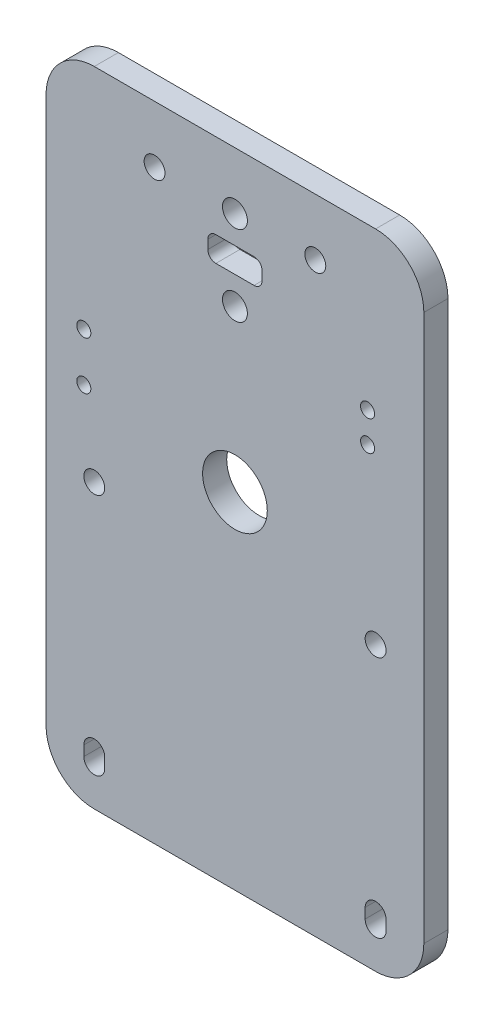
SolidWorks part; units mm, degrees
material "Polycarbonate (PC)"
ref_plane "Спереди" through (0, 0, 0) normal (0, 0, 1) x (1, 0, 0)
ref_plane "Сверху" through (0, 0, 0) normal (0, 1, 0) x (1, 0, 0)
ref_plane "Справа" through (0, 0, 0) normal (1, 0, 0) x (0, 0, -1)
sketch "Model" plane through (0, 0, 0) normal (0, 0, 1) x (1, 0, 0)
  line L5 (0, 170.1561) -> (0, 0) construction
  line L24 (-35, 37.2847) -> (-35, 78.8619) construction
  line L25 (-31.4983, 12.5) -> (-38.4, 12.5) construction
  line L26 (-31.4983, 10) -> (-38.4, 10) construction
  line L27 (-35, 12.5) -> (-35, 10) construction
  line L28 (-32.4, 12.5) -> (-32.4, 10)
  line L29 (-37.6, 12.5) -> (-37.6, 10)
  line L40 (31.4983, 10) -> (38.4, 10) construction
  line L41 (31.4983, 12.5) -> (38.4, 12.5) construction
  line L42 (35, 37.2847) -> (35, 78.8619) construction
  line L43 (35, 12.5) -> (35, 10) construction
  line L44 (32.4, 12.5) -> (32.4, 10)
  line L45 (37.6, 12.5) -> (37.6, 10)
  line L47 (-26.0102, 145.8) -> (26.0946, 145.8) construction
  line L50 (-20, 133.6948) -> (-20, 127.8457) construction
  line L51 (-38.85, 70.45) -> (-29.8907, 70.45) construction
  line L53 (-16.3166, 125.8) -> (17.7871, 125.8) construction
  line L58 (38.85, 70.45) -> (29.8907, 70.45) construction
  line L4875 (-35, 160) -> (35, 160)
  line L4882 (47, 148) -> (47, 12)
  line L4889 (35, 0) -> (-35, 0)
  line L4896 (-47, 12) -> (-47, 148)
  line L6648 (-6.75, 138.9) -> (6.75, 138.9)
  line L6649 (6.75, 138.9) -> (6.75, 132.7)
  line L6650 (6.75, 132.7) -> (-6.75, 132.7)
  line L6651 (-6.75, 132.7) -> (-6.75, 138.9)
  arc A0 (-47, 12) -> (-35, 0) centre (-35, 12) ccw
  arc A1 (35, 0) -> (47, 12) centre (35, 12) ccw
  arc A2 (47, 148) -> (35, 160) centre (35, 148) ccw
  arc A3 (-35, 160) -> (-47, 148) centre (-35, 148) ccw
  arc A13 (-32.4, 12.5) -> (-37.6, 12.5) centre (-35, 12.5) ccw
  arc A14 (-37.6, 10) -> (-32.4, 10) centre (-35, 10) ccw
  arc A19 (32.4, 12.5) -> (37.6, 12.5) centre (35, 12.5) cw
  arc A20 (37.6, 10) -> (32.4, 10) centre (35, 10) cw
  circle A29 centre (0, 145.8) radius 3.1
  circle A30 centre (-20, 145.8) radius 2.6
  circle A31 centre (20, 145.8) radius 2.6
  circle A32 centre (-35, 70.45) radius 2.6
  circle A33 centre (0, 125.8) radius 3.1
  circle A36 centre (35, 70.45) radius 2.6
  point P0 (-6.75, 135.8)
  point P1 (-227.3391, 118.1602)
  point P17 (0, 0)
  point P77 (-35, 11.25)
  point P114 (35, 11.25)
  dimension "D5" = 5.2
  dimension "D8" = 13.5
  dimension "D35" = 6.2
  dimension "D13" = 12
  dimension "D3" = 160
  dimension "D6" = 20
  dimension "D7" = 20
  dimension "D9" = 70
  dimension "D10" = 60.45
  dimension "D11" = 24.2
  dimension "D12" = 94
  dimension "D16" = 2.5
  dimension "D17" = 10
  dimension "D18" = 5.2
  dimension "D25" = 14.2
  dimension "D34" = 20
  dimension "D42" = 6.2
extrude "Base" add sketch "Model" along normal blind 6
sketch "Эскиз1" plane through (0, 0, 0) normal (0, 0, -1) x (-1, 0, 0)
  line L0 (35, 160) -> (-35, 160) construction
  line L1 (0, 160) -> (0, 146.8198) construction
  circle A0 centre (0, 85.8) radius 8.05
  dimension "D2" = 16.1
  dimension "D1" = 74.2
extrude "BearingHole" cut sketch "Эскиз1" against normal blind 10
sketch "Sketch1" plane through (0, 0, 6) normal (0, 0, 1) x (1, 0, 0)
  line L0 (-35, 160) -> (35, 160) construction
  line L1 (47, 148) -> (47, 12) construction
  circle A0 centre (33, 120) radius 1.75
  circle A1 centre (33, 112.5) radius 1.75
  dimension "D1" = 3.5
  dimension "D3" = 7.5
  dimension "D4" = 40
  dimension "D5" = 14
extrude "SensorMount" cut sketch "Sketch1" against normal blind 10
sketch "Sketch3" plane through (0, 0, 0) normal (0, 0, -1) x (-1, 0, 0)
  line L1 (47, 12) -> (47, 148) construction
  line L3 (-35, 0) -> (35, 0) construction
  circle A0 centre (37.6, 90.0886) radius 1.75
  circle A1 centre (37.6, 102.0886) radius 1.75
  dimension "D3" = 3.5
  dimension "D4" = 90.0886
  dimension "D1" = 12
  dimension "D2" = 9.4
extrude "CableMount" cut sketch "Sketch3" against normal blind 10
fillet "FilletCableSlot" radius 2 4 edges at (6.75, 138.9, 3) (-6.75, 138.9, 3) (-6.75, 132.7, 3) (6.75, 132.7, 3)
ref_plane "Plane1" through (0, 40.225, 0) normal (0, -1, 0) x (-1, 0, 0)
